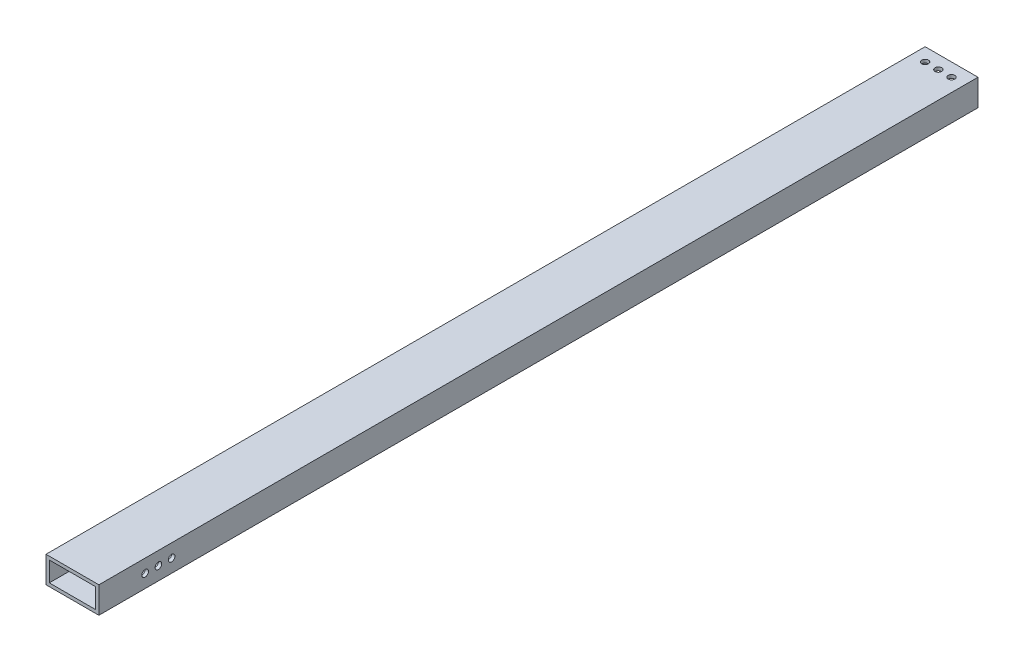
SolidWorks part; units mm, degrees
ref_plane "Front Plane" through (0, 0, 0) normal (0, 0, 1) x (1, 0, 0)
ref_plane "Top Plane" through (0, 0, 0) normal (0, 1, 0) x (1, 0, 0)
ref_plane "Right Plane" through (0, 0, 0) normal (1, 0, 0) x (0, 0, -1)
sketch "Sketch1" plane through (0, 0, 0) normal (0, 0, 1) x (1, 0, 0)
  line L0 (3.175, 22.225) -> (47.625, 22.225)
  line L1 (0, 0) -> (50.8, 0)
  line L2 (0, 0) -> (0, 25.4)
  line L3 (0, 25.4) -> (50.8, 25.4)
  line L4 (50.8, 0) -> (50.8, 25.4)
  line L5 (47.625, 3.175) -> (47.625, 22.225)
  line L6 (3.175, 3.175) -> (47.625, 3.175)
  line L7 (3.175, 3.175) -> (3.175, 22.225)
  dimension "D1" = 50.8
  dimension "D2" = 25.4
  dimension "D3" = 3.175
extrude "Boss-Extrude1" add sketch "Sketch1" along normal blind 844.55
sketch "Sketch2" plane through (50.8, 0, 0) normal (1, 0, 0) x (0, 0, -1)
  line L0 (-800.1, 12.7) -> (-844.55, 12.7) construction
  line L1 (-844.55, 0) -> (-844.55, 25.4) construction
  circle A0 centre (-800.1, 12.7) radius 3.175
  circle A1 centre (-787.4, 12.7) radius 3.175
  circle A2 centre (-774.7, 12.7) radius 3.175
  dimension "D2" = 6.35
  dimension "D1" = 44.45
  dimension "D4" = 12.7
  dimension "D3" = 3
extrude "Cut-Extrude1" cut sketch "Sketch2" against normal through all both and the other way through all
hole_wizard "1/4 (0.25) Diameter Hole3" positions "Sketch8" profile "Sketch9" hole size "1/4" standard "ANSI Inch" end condition through all
sketch "Sketch8" plane through (0, 25.4, 0) normal (0, 1, 0) x (1, 0, 0)
  line L0 (12.7, -12.7) -> (25.4, -12.7)
  line L1 (25.4, -12.7) -> (38.1, -12.7)
  line L3 (50.8, 0) -> (0, 0) construction
  line L4 (0, -844.55) -> (0, 0) construction
  point P0 (12.7, -12.7)
  point P2 (25.4, -12.7)
  point P4 (38.1, -12.7)
  dimension "D1" = 12.7
  dimension "0.5" = 12.7
  dimension "D2" = 12.7
sketch "Sketch9" plane through (12.7, 25.4, 12.7) normal (1, 0, 0) x (0, 0, 1)
  line L0 (0, 0) -> (0, 25.4)
  line L1 (0, 25.4) -> (3.175, 25.4)
  line L2 (3.175, 25.4) -> (3.175, 0)
  line L5 (3.175, 0) -> (0, 0)
  line L11 (0, -6.35) -> (0, 107.95) construction
  dimension "Thru Hole Dia." = 6.35
  dimension "Thru Hole Depth" = 25.4
